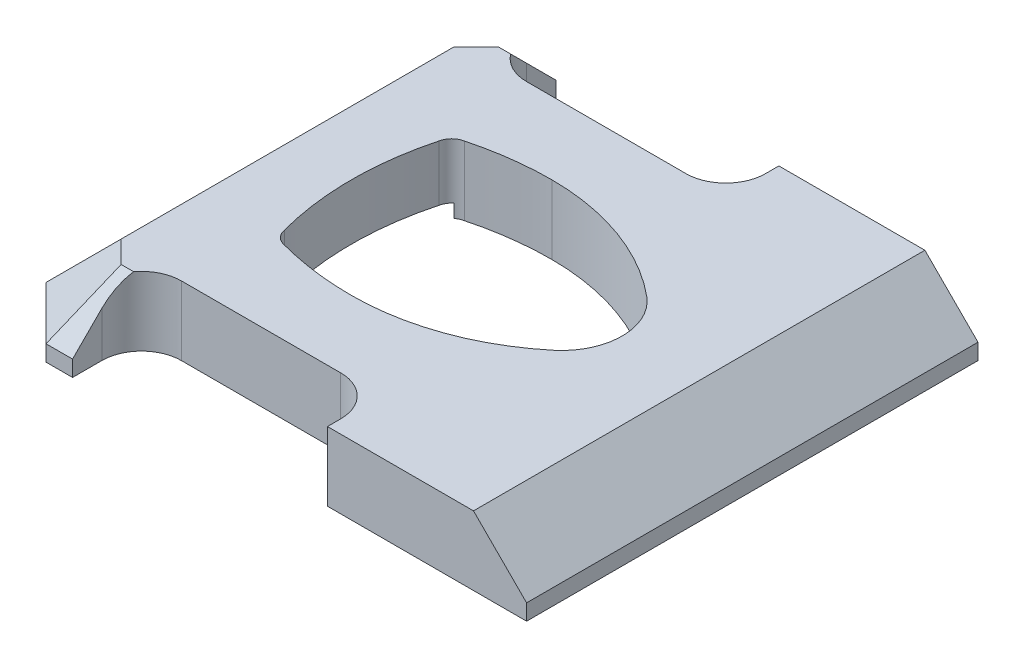
SolidWorks part; units mm, degrees
material "ABS"
ref_plane "Front Plane" through (0, 0, 0) normal (0, 0, 1) x (1, 0, 0)
ref_plane "Top Plane" through (0, 0, 0) normal (0, 1, 0) x (1, 0, 0)
ref_plane "Right Plane" through (0, 0, 0) normal (1, 0, 0) x (0, 0, -1)
sketch "Sketch1" plane through (0, 0, 0) normal (0, 1, 0) x (1, 0, 0)
  line L1 (-97.5, 85) -> (97.5, 85)
  line L2 (-97.5, 85) -> (-97.5, -85)
  line L3 (-97.5, -85) -> (97.5, -85)
  line L4 (97.5, 85) -> (97.5, -85)
  line L5 (-97.5, 85) -> (97.5, -85) construction
  line L6 (-97.5, -85) -> (97.5, 85) construction
  point P0 (0, 0)
  dimension "D1" = 195
  dimension "D2" = 170
extrude "Boss-Extrude1" add sketch "Sketch1" along normal blind 26
sketch "Sketch2" plane through (0, 26, 0) normal (0, 1, 0) x (1, 0, 0)
  line L0 (-97.5, -85) -> (-67.5, -85) construction
  line L1 (-97.5, -85) -> (97.5, -85) construction
  line L2 (0, 0) -> (-97.5, 0) construction
  line L3 (-67.5, -85) -> (22.5, -85)
  line L4 (-67.5, -85) -> (-67.5, -65)
  line L5 (-67.5, -65) -> (22.5, -65)
  line L6 (22.5, -85) -> (22.5, -65)
  line L7 (-97.5, 85) -> (-97.5, -85) construction
  line L8 (-67.5, 65) -> (22.5, 65)
  line L9 (22.5, 85) -> (22.5, 65)
  line L10 (-67.5, 85) -> (22.5, 85)
  line L11 (-67.5, 85) -> (-67.5, 65)
  dimension "D1" = 30
  dimension "D2" = 90
  dimension "D3" = 20
extrude "Cut-Extrude1" cut sketch "Sketch2" against normal through all
fillet "Fillet1" radius 15 4 edges at (22.5, 13, -65) (-67.5, 13, -65) (-67.5, 13, 65) (22.5, 13, 65)
sketch "Sketch3" plane through (0, 26, 0) normal (0, 1, 0) x (1, 0, 0)
  line L0 (0, 0) -> (-97.5, 0) construction
  line L1 (-67.5, 85) -> (-97.5, 85)
  line L2 (-67.5, 85) -> (-67.5, 91)
  line L3 (-67.5, 91) -> (-97.5, 91)
  line L4 (-97.5, 85) -> (-97.5, 91)
  line L5 (-97.5, 85) -> (-97.5, -85) construction
  line L6 (-67.5, -91) -> (-97.5, -91)
  line L7 (-97.5, -85) -> (-97.5, -91)
  line L8 (-67.5, -85) -> (-97.5, -85)
  line L9 (-67.5, -85) -> (-67.5, -91)
  dimension "D1" = 6
extrude "Boss-Extrude2" add sketch "Sketch3" against normal up to surface (26 mm away) up to face at (-16.875, 0, 0)
chamfer "Chamfer1" distance 20 angle 45 2 edges at (-97.5, 13, 91) (-97.5, 13, -91)
chamfer "Chamfer2" distance 20 angle 45 5 edges at (-72.5, 26, 91) (-72.5, 26, -91) (-97.5, 26, 0) (-87.5, 26, 81) (-87.5, 26, -81)
chamfer "Chamfer3" distance 20 angle 45 1 edges at (97.5, 26, 0)
sketch "Sketch6" plane through (0, 0, 0) normal (0, -1, 0) x (1, 0, 0)
  line L0 (51.5, -75) -> (82.1667, -75) construction
  line L5 (143.5, -85) -> (51.5, -85) construction
  line L6 (143.5, -85) -> (143.5, -65) construction
  line L7 (143.5, -65) -> (51.5, -65) construction
  line L8 (51.5, -85) -> (51.5, -65) construction
  line L9 (82.1667, -75) -> (112.8333, -75) construction
  line L10 (112.8333, -75) -> (143.5, -75) construction
  line L11 (0, 0) -> (97.5, 0) construction
  line L12 (97.5, 85) -> (97.5, -85) construction
  line L13 (97.5, -85) -> (22.5, -85) construction
  line L14 (-77.5, -91) -> (-67.5, -91) construction
  line L15 (-67.5, -91) -> (-67.5, -80) construction
  circle A2 centre (82.1667, -75) radius 6.1
  circle A3 centre (82.1667, 75) radius 6.1
  circle A4 centre (-75.5, -79.6) radius 6.1
  circle A5 centre (-75.5, 79.6) radius 6.1
  point P6 (97.5, -75)
  dimension "D3" = 12.2
  dimension "D6" = 12.2
  dimension "D1" = 92
  dimension "D2" = 20
  dimension "D4" = 11.4
  dimension "D5" = 8
extrude "Cut-Extrude4" cut sketch "Sketch6" against normal blind 3.2
fillet "Fillet2" radius 0.2 4 edges at (-75.5, 0, 85.7) (-75.5, 0, -85.7) (82.1667, 0, -81.1) (82.1667, 0, 81.1)
sketch "Sketch4" plane through (-97.5, 0, 0) normal (-1, 0, 0) x (0, 0, 1)
  line L0 (-30.05, 16) -> (30.05, 16) construction
  line L1 (71, 6) -> (-71, 6) construction
  circle A0 centre (-30.05, 16) radius 7
  circle A1 centre (30.05, 16) radius 7
  point P4 (0, 16)
  dimension "D1" = 14
  dimension "D2" = 14
  dimension "D3" = 60.1
  dimension "D4" = 10
sketch "Sketch5" plane through (0, 0, 0) normal (0, -1, 0) x (1, 0, 0)
  line L0 (0, 0) -> (-97.5, 0) construction
  line L1 (-93.5, 38.3) -> (-77.5, 38.3)
  line L2 (-93.5, 38.3) -> (-93.5, 21.8) construction
  line L3 (-93.5, 21.8) -> (-77.5, 21.8)
  line L4 (-77.5, 38.3) -> (-77.5, 21.8) construction
  line L5 (-93.5, 38.3) -> (-77.5, 21.8) construction
  line L6 (-93.5, 21.8) -> (-77.5, 38.3) construction
  line L7 (-93.5, -21.8) -> (-77.5, -21.8)
  line L8 (-93.5, -21.8) -> (-93.5, -38.3) construction
  line L9 (-93.5, -38.3) -> (-77.5, -38.3)
  line L10 (-77.5, -21.8) -> (-77.5, -38.3) construction
  line L11 (-93.5, -21.8) -> (-77.5, -38.3) construction
  line L12 (-93.5, -38.3) -> (-77.5, -21.8) construction
  line L13 (-97.5, -71) -> (-97.5, 71) construction
  line L14 (-85.5, 30.05) -> (-85.5, -30.05) construction
  line L15 (-77.5, 38.3) -> (-57.5, 38.3) construction
  line L16 (-57.5, 38.3) -> (-57.5, -38.3)
  line L17 (-57.5, -38.3) -> (-77.5, -38.3) construction
  line L18 (-77.5, 21.8) -> (-77.5, -21.8)
  line L20 (-77.5, -38.3) -> (-57.5, -38.3) construction
  line L21 (-77.5, -38.3) -> (-77.5, -53.3)
  line L22 (-77.5, -53.3) -> (-57.5, -53.3)
  line L23 (-57.5, -38.3) -> (-57.5, -53.3)
  line L24 (-77.5, 38.3) -> (-57.5, 38.3) construction
  line L25 (-77.5, 38.3) -> (-77.5, 53.3)
  line L26 (-77.5, 53.3) -> (-57.5, 53.3)
  line L27 (-57.5, 38.3) -> (-57.5, 53.3)
  line L28 (-93.5, 38.3) -> (-96.5, 38.3)
  line L29 (-93.5, 38.3) -> (-93.5, 21.8) construction
  line L30 (-93.5, 21.8) -> (-96.5, 21.8)
  line L31 (-96.5, 38.3) -> (-96.5, 21.8)
  line L32 (-93.5, -21.8) -> (-96.5, -21.8)
  line L33 (-93.5, -21.8) -> (-93.5, -38.3) construction
  line L34 (-93.5, -38.3) -> (-96.5, -38.3)
  line L35 (-96.5, -21.8) -> (-96.5, -38.3)
  point P0 (-85.5, 30.05)
  point P5 (-85.5, -30.05)
  point P17 (-85.5, 0)
  dimension "D1" = 20
  dimension "D2" = 16
  dimension "D3" = 16.5
  dimension "D4" = 16.5
  dimension "D5" = 60.1
  dimension "D6" = 12
  dimension "D7" = 15
  dimension "D8" = 15
  dimension "D9" = 3
extrude "Cut-Extrude3" cut sketch "Sketch5" against normal blind 23
sketch "Sketch7" plane through (0, 0, 0) normal (0, -1, 0) x (1, 0, 0)
  line L0 (97.5, -85) -> (22.5, -85) construction
  line L1 (97.5, 85) -> (97.5, -85) construction
  line B0 (-50.4814, 0) -> (45.4814, 0) construction
  arc B1 (-44.5394, -30.8943) -> (-44.2077, -30.9649) centre (-43.75, -28) ccw construction
  arc B2 (-46.6443, -28.7894) -> (-44.5394, -30.8943) centre (-43.75, -28) ccw construction
  arc B3 (-46.7149, -28.4577) -> (-46.6443, -28.7894) centre (-43.75, -28) ccw construction
  arc B4 (-44.2077, 30.9649) -> (-44.5394, 30.8943) centre (-43.75, 28) ccw construction
  arc B5 (-44.5394, 30.8943) -> (-46.6443, 28.7894) centre (-43.75, 28) ccw construction
  arc B6 (-46.6443, 28.7894) -> (-46.7149, 28.4577) centre (-43.75, 28) ccw construction
  arc B7 (-46.7149, 28.4577) -> (-46.7149, -28.4577) centre (58.9083, 0) ccw construction
  arc B8 (-44.2077, -30.9649) -> (-15.75, -34.7314) centre (-15.75, 74.6583) ccw construction
  arc B9 (-15.75, -34.7314) -> (38.3655, -15.1715) centre (-15.75, 49.9083) ccw construction
  arc B10 (38.3655, -15.1715) -> (38.3655, 15.1715) centre (25.75, 0) ccw construction
  arc B11 (38.3655, 15.1715) -> (-15.75, 34.7314) centre (-15.75, -49.9083) ccw construction
  arc B12 (-15.75, 34.7314) -> (-44.2077, 30.9649) centre (-15.75, -74.6583) ccw construction
  arc B13 (-45.3288, -33.7886) -> (-44.855, -33.8974) centre (-43.75, -28) ccw
  arc B14 (-44.855, -33.8974) -> (-15.75, -37.7314) centre (-15.75, 74.6583) ccw
  arc B15 (-15.75, -37.7314) -> (40.2836, -17.4782) centre (-15.75, 49.9083) ccw
  arc B16 (40.2836, -17.4782) -> (40.2836, 17.4782) centre (25.75, 0) ccw
  arc B17 (40.2836, 17.4782) -> (-15.75, 37.7314) centre (-15.75, -49.9083) ccw
  arc B18 (-15.75, 37.7314) -> (-44.855, 33.8974) centre (-15.75, -74.6583) ccw
  arc B19 (-44.855, 33.8974) -> (-45.3288, 33.7886) centre (-43.75, 28) ccw
  arc B20 (-45.3288, 33.7886) -> (-49.5386, 29.5788) centre (-43.75, 28) ccw
  arc B21 (-49.5386, 29.5788) -> (-49.6474, 29.105) centre (-43.75, 28) ccw
  arc B22 (-49.6474, 29.105) -> (-49.6474, -29.105) centre (58.9083, 0) ccw
  arc B23 (-49.6474, -29.105) -> (-49.5386, -29.5788) centre (-43.75, -28) ccw
  arc B24 (-49.5386, -29.5788) -> (-45.3288, -33.7886) centre (-43.75, -28) ccw
  dimension "D1" = 85
  dimension "D2" = 100
sketch_block_instance "Block2-1"
sketch_block "Block2" parameters "D1"=3
extrude "Cut-Extrude5" cut sketch "Sketch7" against normal through all
sketch "Sketch8" plane through (0, 0, 0) normal (0, -1, 0) x (1, 0, 0)
  line L0 (-96.5, -38.3) -> (-77.5, -38.3) construction
  line L1 (-96.5, 38.3) -> (-91.5, 38.3)
  line L2 (-96.5, 38.3) -> (-96.5, -38.3)
  line L3 (-96.5, -38.3) -> (-91.5, -38.3)
  line L4 (-91.5, 38.3) -> (-91.5, -38.3)
  dimension "D1" = 5
extrude "Boss-Extrude3" add sketch "Sketch8" against normal up to vertex (7 mm away)
sketch "Sketch9" plane through (0, 0, 0) normal (0, -1, 0) x (1, 0, 0)
  line L0 (-77.5, -53.3) -> (-57.5, -53.3) construction
  line L1 (-57.5, 53.3) -> (-47.5, 53.3)
  line L2 (-57.5, 53.3) -> (-57.5, -53.3)
  line L3 (-57.5, -53.3) -> (-47.5, -53.3)
  line L4 (-47.5, 53.3) -> (-47.5, -53.3)
  dimension "D1" = 10
extrude "Cut-Extrude6" cut sketch "Sketch9" against normal blind 5
sketch "Sketch10" plane through (0, 0, 0) normal (0, -1, 0) x (1, 0, 0)
  line L0 (-77.5, -53.3) -> (-47.5, -53.3) construction
  line L1 (-77.5, 53.3) -> (-80.5, 53.3)
  line L2 (-77.5, 53.3) -> (-77.5, -53.3)
  line L3 (-77.5, -53.3) -> (-80.5, -53.3)
  line L4 (-80.5, 53.3) -> (-80.5, -53.3)
  dimension "D1" = 3
extrude "Cut-Extrude7" cut sketch "Sketch10" against normal blind 20
sketch "Sketch13" plane through (0, 0, 38.3) normal (0, 0, -1) x (-1, 0, 0)
  line L0 (80.5, 23) -> (77.5, 23)
  line L1 (77.5, 23) -> (77.5, 22)
  line L2 (77.5, 23) -> (77.5, 20) construction
  line L3 (77.5, 22) -> (81.5, 22)
  line L4 (96.5, 7) -> (80.5, 23) construction
  line L5 (81.5, 22) -> (80.5, 23)
  dimension "D1" = 1
extrude "Boss-Extrude8" add sketch "Sketch13" along normal up to surface (76.6 mm away) up to face at (-84.5, 12.5, -38.3)
sketch "Sketch14" plane through (0, 7, 0) normal (0, 1, 0) x (1, 0, 0)
  line L0 (-91.5, -21.8) -> (-96.5, -21.8) construction
  line L1 (-91.5, 21.8) -> (-97.5, 21.8)
  line L2 (-91.5, 21.8) -> (-91.5, 38.3)
  line L3 (-91.5, 38.3) -> (-97.5, 38.3)
  line L4 (-97.5, 21.8) -> (-97.5, 38.3)
  line L5 (-91.5, -38.3) -> (-97.5, -38.3)
  line L6 (-91.5, -38.3) -> (-91.5, -21.8)
  line L7 (-91.5, -21.8) -> (-97.5, -21.8)
  line L8 (-97.5, -38.3) -> (-97.5, -21.8)
  line L9 (-96.5, 38.3) -> (-91.5, 38.3) construction
  line L10 (-97.5, -71) -> (-97.5, 71) construction
extrude "Cut-Extrude9" cut sketch "Sketch14" against normal blind 0.5
sketch "Sketch15" plane through (0, 0, 0) normal (0, -1, 0) x (1, 0, 0)
  line L0 (-80.5, 21.8) -> (-80.5, -21.8) construction
  line L1 (-80.5, 11.8) -> (-85.5, 11.8)
  line L2 (-80.5, 11.8) -> (-80.5, -11.8)
  line L3 (-80.5, -11.8) -> (-85.5, -11.8)
  line L4 (-85.5, 11.8) -> (-85.5, -11.8)
  line L5 (-80.5, -21.8) -> (-91.5, -21.8) construction
  line L6 (-91.5, 21.8) -> (-80.5, 21.8) construction
  dimension "D1" = 10
  dimension "D2" = 10
  dimension "D3" = 5
extrude "Cut-Extrude10" cut sketch "Sketch15" against normal blind 10
sketch "Sketch16" plane through (0, 23, 0) normal (0, -1, 0) x (1, 0, 0)
  line L1 (-77.5, 53.3) -> (-57.5, 53.3)
  line L2 (-77.5, 53.3) -> (-77.5, -53.3)
  line L3 (-77.5, -53.3) -> (-57.5, -53.3)
  line L4 (-57.5, 53.3) -> (-57.5, -53.3)
extrude "Cut-Extrude11" cut sketch "Sketch16" against normal blind 1
